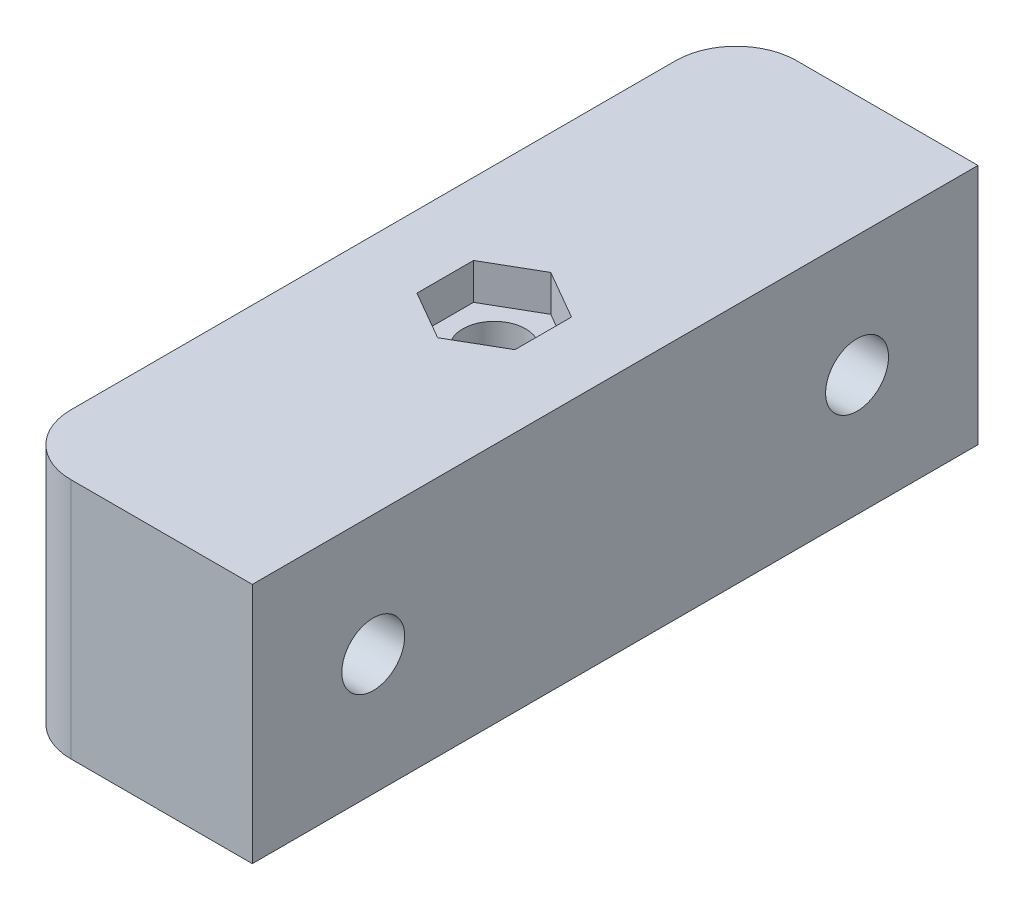
SolidWorks part; units mm, degrees
material "ABS"
ref_plane "Front Plane" through (0, 0, 0) normal (0, 0, 1) x (1, 0, 0)
ref_plane "Top Plane" through (0, 0, 0) normal (0, 1, 0) x (1, 0, 0)
ref_plane "Right Plane" through (0, 0, 0) normal (1, 0, 0) x (0, 0, -1)
sketch "Sketch1" plane through (0, 0, 0) normal (0, 1, 0) x (1, 0, 0)
  line L0 (0, 0) -> (0, 30)
  line L1 (0, 30) -> (-20, 30)
  line L2 (-20, 30) -> (-20, -30)
  line L3 (-20, -30) -> (0, -30)
  line L4 (0, -30) -> (0, 0)
  dimension "D1" = 60
  dimension "D2" = 20
extrude "Boss-Extrude1" add sketch "Sketch1" along normal blind 20
sketch "Sketch4" plane through (0, 20, 0) normal (0, 1, 0) x (1, 0, 0)
  line L0 (0, 0) -> (-20, 0) construction
  line L1 (-20, 30) -> (-20, -30) construction
  circle A0 centre (-10, 0) radius 2.6
  dimension "D1" = 5.2
extrude "Cut-Extrude1" cut sketch "Sketch4" against normal through all
sketch "Sketch5" plane through (0, 20, 0) normal (0, 1, 0) x (1, 0, 0)
  line L1 (-10, 4.6765) -> (-14.05, 2.3383)
  line L2 (-14.05, 2.3383) -> (-14.05, -2.3383)
  line L3 (-14.05, -2.3383) -> (-10, -4.6765)
  line L4 (-10, -4.6765) -> (-5.95, -2.3383)
  line L5 (-5.95, -2.3383) -> (-5.95, 2.3383)
  line L6 (-5.95, 2.3383) -> (-10, 4.6765)
  circle A0 centre (-10, 0) radius 4.05 construction
  dimension "D1" = 8.1
extrude "Cut-Extrude2" cut sketch "Sketch5" against normal blind 3
sketch "Sketch6" plane through (0, 0, 0) normal (0, -1, 0) x (1, 0, 0)
  line L1 (-10, -4.6765) -> (-5.95, -2.3383)
  line L2 (-5.95, -2.3383) -> (-5.95, 2.3383)
  line L3 (-5.95, 2.3383) -> (-10, 4.6765)
  line L4 (-10, 4.6765) -> (-14.05, 2.3383)
  line L5 (-14.05, 2.3383) -> (-14.05, -2.3383)
  line L6 (-14.05, -2.3383) -> (-10, -4.6765)
  circle A0 centre (-10, 0) radius 4.05 construction
  dimension "D1" = 8.1
extrude "Cut-Extrude3" cut sketch "Sketch6" against normal blind 8
sketch "Sketch7" plane through (0, 0, 0) normal (1, 0, 0) x (0, 0, -1)
  line L0 (-30, 10) -> (-20, 10) construction
  line L1 (-30, 20) -> (-30, 0) construction
  line L2 (-20, 10) -> (20, 10) construction
  line L3 (20, 10) -> (30, 10) construction
  line L4 (30, 20) -> (30, 0) construction
  circle A0 centre (-20, 10) radius 2.6
  circle A1 centre (20, 10) radius 2.6
  dimension "D1" = 5.2
  dimension "D2" = 40
extrude "Cut-Extrude4" cut sketch "Sketch7" against normal through all
fillet "Fillet1" radius 5 2 edges at (-20, 10, -30) (-20, 10, 30)
